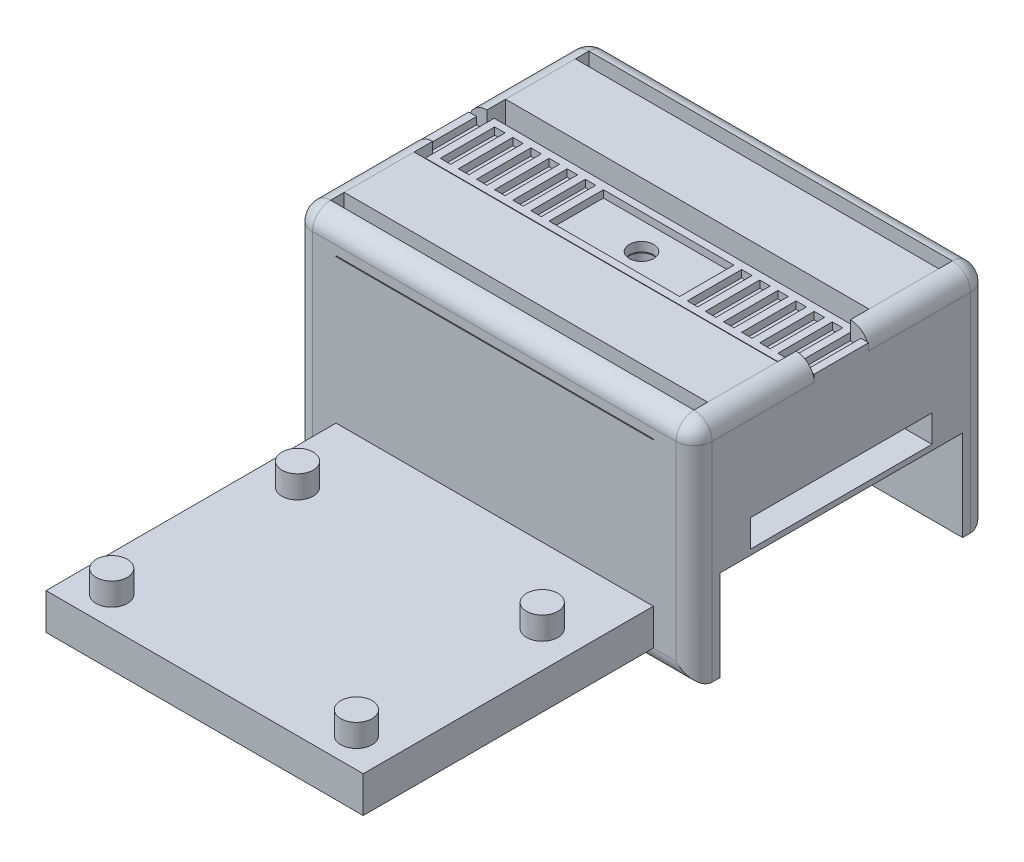
SolidWorks part; units mm, degrees
ref_plane "Front Plane" through (0, 0, 0) normal (0, 0, 1) x (1, 0, 0)
ref_plane "Top Plane" through (0, 0, 0) normal (0, 1, 0) x (1, 0, 0)
ref_plane "Right Plane" through (0, 0, 0) normal (1, 0, 0) x (0, 0, -1)
sketch "Sketch1" plane through (0, 0, 0) normal (0, 1, 0) x (1, 0, 0)
  line L1 (-22.05, 16.25) -> (22.05, 16.25)
  line L2 (-22.05, 16.25) -> (-22.05, -16.25)
  line L3 (-22.05, -16.25) -> (22.05, -16.25)
  line L4 (22.05, 16.25) -> (22.05, -16.25)
  line L5 (-22.05, 16.25) -> (22.05, -16.25) construction
  line L6 (-22.05, -16.25) -> (22.05, 16.25) construction
  point P0 (0, 0)
  dimension "D1" = 44.1
  dimension "D2" = 32.5
extrude "Boss-Extrude1" add sketch "Sketch1" along normal blind 25
sketch "Sketch2" plane through (0, 0, 0) normal (0, -1, 0) x (1, 0, 0)
  line L0 (22.05, 16.25) -> (22.05, -16.25) construction
  line L1 (-22.05, -13.375) -> (22.05, -13.375)
  line L2 (-22.05, -13.375) -> (-22.05, 13.375)
  line L3 (-22.05, 13.375) -> (22.05, 13.375)
  line L4 (22.05, -13.375) -> (22.05, 13.375)
  line L5 (-22.05, -13.375) -> (22.05, 13.375) construction
  line L6 (-22.05, 13.375) -> (22.05, -13.375) construction
  point P0 (0, 0)
  dimension "D1" = 26.75
extrude "Cut-Extrude1" cut sketch "Sketch2" against normal blind 10
fillet "Fillet1" radius 2 10 edges at (0, 25, -16.25) (22.05, 12.5, -16.25) (-22.05, 12.5, -16.25) (-22.05, 12.5, 16.25) (22.05, 12.5, 16.25) (0, 25, 16.25) (22.05, 25, 0) (-22.05, 25, 0) (0, 0, -16.25) (0, 0, 16.25)
sketch "Sketch6" plane through (0, 0, 0) normal (1, 0, 0) x (0, 0, -1)
  line L0 (14.25, 23) -> (-14.25, 23) construction
  line L1 (-10, 10.6) -> (10, 10.6)
  line L2 (-10, 10.6) -> (-10, 13.6)
  line L3 (-10, 13.6) -> (10, 13.6)
  line L4 (10, 10.6) -> (10, 13.6)
  line L5 (-10, 10.6) -> (10, 13.6) construction
  line L6 (-10, 13.6) -> (10, 10.6) construction
  line L12 (13.375, 10) -> (-13.375, 10) construction
  line L13 (-14.25, 25) -> (14.25, 25) construction
  line L14 (-3, 23) -> (3, 23)
  line L15 (-3, 23) -> (-3, 25)
  line L16 (-3, 25) -> (3, 25)
  line L17 (3, 23) -> (3, 25)
  line L18 (-3, 23) -> (3, 25) construction
  line L19 (-3, 25) -> (3, 23) construction
  point P0 (0, 12.1)
  point P8 (0, 10)
  point P11 (0, 24)
  point P20 (0, 23)
  dimension "D1" = 20
  dimension "D3" = 3
  dimension "D4" = 0.6
  dimension "D5" = 2
  dimension "D6" = 6
extrude "Cut-Extrude2" cut sketch "Sketch6" against normal through all both and the other way through all
sketch "Sketch7" plane through (0, 25, 0) normal (0, 1, 0) x (1, 0, 0)
  line L0 (-20.05, 14.25) -> (-20.05, 3) construction
  line L1 (-20.05, 5.05) -> (20.05, 5.05)
  line L2 (-20.05, 5.05) -> (-20.05, 3.8)
  line L3 (-20.05, 3.8) -> (20.05, 3.8)
  line L4 (20.05, 5.05) -> (20.05, 3.8)
  line L5 (20.05, 3) -> (20.05, 14.25) construction
  line L6 (-20.05, -3) -> (-20.05, -14.25) construction
  line L7 (-20.05, -3.8) -> (20.05, -3.8)
  line L8 (-20.05, -3.8) -> (-20.05, -5.05)
  line L9 (-20.05, -5.05) -> (20.05, -5.05)
  line L10 (20.05, -3.8) -> (20.05, -5.05)
  line L11 (20.05, -14.25) -> (20.05, -3) construction
  line L12 (-22.05, 3) -> (22.05, 3) construction
  line L13 (-22.05, -3) -> (22.05, -3) construction
  dimension "D1" = 1.25
  dimension "D2" = 0.8
  dimension "D3" = 0.8
  dimension "D4" = 1.25
extrude "Cut-Extrude3" cut sketch "Sketch7" against normal blind 5.5
sketch "Sketch8" plane through (0, 23, 0) normal (0, 1, 0) x (1, 0, 0)
  line L0 (0, 11.2553) -> (0, -14.25) construction
  line L1 (-20.05, -14.25) -> (20.05, -14.25) construction
  line L2 (-22.05, -3) -> (22.05, -3) construction
  line L3 (-22.05, 3) -> (-21.2, 3)
  line L4 (-22.05, 3) -> (-22.05, -3)
  line L5 (-22.05, -3) -> (-21.2, -3)
  line L6 (-21.2, 3) -> (-21.2, -3)
  line L7 (22.05, 3) -> (22.05, -3)
  line L8 (22.05, 3) -> (21.2, 3)
  line L9 (21.2, 3) -> (21.2, -3)
  line L10 (22.05, -3) -> (21.2, -3)
  line L11 (-22.05, 3) -> (22.05, 3) construction
  line L12 (-20.05, 3) -> (-19.2, 3)
  line L13 (-20.05, 3) -> (-20.05, -3)
  line L14 (-20.05, -3) -> (-19.2, -3)
  line L15 (-19.2, 3) -> (-19.2, -3)
  line L16 (20.05, 3) -> (20.05, -3)
  line L17 (20.05, 3) -> (19.2, 3)
  line L18 (19.2, 3) -> (19.2, -3)
  line L19 (20.05, -3) -> (19.2, -3)
  line L20 (-20.05, 3) -> (20.05, 3) construction
  line L21 (-18.05, 3) -> (-17.2, 3)
  line L22 (-18.05, 3) -> (-18.05, -3)
  line L23 (-18.05, -3) -> (-17.2, -3)
  line L24 (-17.2, 3) -> (-17.2, -3)
  line L25 (-20.05, -3) -> (20.05, -3) construction
  line L26 (18.05, 3) -> (18.05, -3)
  line L27 (18.05, 3) -> (17.2, 3)
  line L28 (17.2, 3) -> (17.2, -3)
  line L29 (18.05, -3) -> (17.2, -3)
  line L30 (16.05, 3) -> (16.05, -3)
  line L31 (-16.05, 3) -> (-15.2, 3)
  line L32 (-16.05, 3) -> (-16.05, -3)
  line L33 (-16.05, -3) -> (-15.2, -3)
  line L34 (-15.2, 3) -> (-15.2, -3)
  line L35 (16.05, 3) -> (15.2, 3)
  line L36 (15.2, 3) -> (15.2, -3)
  line L37 (16.05, -3) -> (15.2, -3)
  line L38 (14.05, 3) -> (14.05, -3)
  line L39 (-14.05, 3) -> (-13.2, 3)
  line L40 (-14.05, 3) -> (-14.05, -3)
  line L41 (-14.05, -3) -> (-13.2, -3)
  line L42 (-13.2, 3) -> (-13.2, -3)
  line L43 (14.05, 3) -> (13.2, 3)
  line L44 (13.2, 3) -> (13.2, -3)
  line L45 (14.05, -3) -> (13.2, -3)
  line L46 (12.05, 3) -> (12.05, -3)
  line L47 (-12.05, 3) -> (-11.2, 3)
  line L48 (-12.05, 3) -> (-12.05, -3)
  line L49 (-12.05, -3) -> (-11.2, -3)
  line L50 (-11.2, 3) -> (-11.2, -3)
  line L51 (12.05, 3) -> (11.2, 3)
  line L52 (11.2, 3) -> (11.2, -3)
  line L53 (12.05, -3) -> (11.2, -3)
  line L54 (10.05, 3) -> (10.05, -3)
  line L55 (-10.05, 3) -> (-9.2, 3)
  line L56 (-10.05, 3) -> (-10.05, -3)
  line L57 (-10.05, -3) -> (-9.2, -3)
  line L58 (-9.2, 3) -> (-9.2, -3)
  line L59 (10.05, 3) -> (9.2, 3)
  line L60 (9.2, 3) -> (9.2, -3)
  line L61 (10.05, -3) -> (9.2, -3)
  line L62 (8.05, 3) -> (8.05, -3)
  line L63 (-8.05, 3) -> (-7.2, 3)
  line L64 (-8.05, 3) -> (-8.05, -3)
  line L65 (-8.05, -3) -> (-7.2, -3)
  line L66 (-7.2, 3) -> (-7.2, -3)
  line L67 (8.05, 3) -> (7.2, 3)
  line L68 (7.2, 3) -> (7.2, -3)
  line L69 (8.05, -3) -> (7.2, -3)
  point P77 (-13.625, 3)
  point P78 (-11.625, 3)
  point P79 (-21.625, 3)
  point P80 (-19.625, 3)
  point P81 (-17.625, 3)
  point P82 (-15.625, 3)
  point P83 (-9.625, 3)
  point P84 (-7.625, 3)
  dimension "D1" = 0.85
  dimension "D2" = 2
  dimension "D3" = 2
  dimension "D4" = 2
  dimension "D5" = 2
  dimension "D6" = 2
  dimension "D7" = 2
  dimension "D8" = 2
extrude "Boss-Extrude3" add sketch "Sketch8" along normal blind 0.8
sketch "Sketch9" plane through (0, 23, 0) normal (0, 1, 0) x (1, 0, 0)
  circle A0 centre (0, 0) radius 1.35
  dimension "D1" = 2.7
extrude "Cut-Extrude4" cut sketch "Sketch9" against normal blind 4
sketch "Sketch11" plane through (0, 0, 3) normal (0, 0, -1) x (-1, 0, 0)
  line L1 (-20.05, 25) -> (20.05, 25)
  line L2 (-20.05, 25) -> (-20.05, 23.8)
  line L3 (-20.05, 23.8) -> (20.05, 23.8)
  line L4 (20.05, 25) -> (20.05, 23.8)
extrude "Cut-Extrude5" cut sketch "Sketch11" against normal up to surface (0.8 mm away) up to face at (0, 22.25, 3.8)
sketch "Sketch12" plane through (0, 0, -3) normal (0, 0, 1) x (1, 0, 0)
  line L1 (-20.05, 25) -> (20.05, 25)
  line L2 (-20.05, 25) -> (-20.05, 23.8)
  line L3 (-20.05, 23.8) -> (20.05, 23.8)
  line L4 (20.05, 25) -> (20.05, 23.8)
extrude "Cut-Extrude6" cut sketch "Sketch12" against normal up to surface (0.8 mm away) up to face at (0, 22.25, -3.8)
sketch "Sketch13" plane through (0, 0, -16.25) normal (0, 0, -1) x (-1, 0, 0)
  line L1 (-17.55, 22) -> (17.45, 22)
  line L2 (-17.55, 22) -> (-17.55, 21.9)
  line L3 (-17.55, 21.9) -> (17.45, 21.9)
  line L4 (17.45, 22) -> (17.45, 21.9)
  line L5 (20.05, 23) -> (-20.05, 23) construction
  line L6 (-20.05, 23) -> (-20.05, 2) construction
  dimension "D1" = 0.1
  dimension "D2" = 1
  dimension "D3" = 35
  dimension "D4" = 2.5
extrude "Cut-Extrude8" cut sketch "Sketch13" against normal through all
sketch "Sketch14" plane through (0, 0, 16.25) normal (0, 0, 1) x (1, 0, 0)
  line L0 (-17.45, 6) -> (17.55, 6)
  line L1 (17.55, 6) -> (17.55, 2)
  line L2 (17.55, 2) -> (-17.45, 2)
  line L3 (-17.45, 2) -> (-17.45, 6)
  line L4 (17.55, 22) -> (17.55, 21.9) construction
  line L5 (22.05, 0) -> (-22.05, 0) construction
  dimension "D1" = 4
  dimension "D2" = 2
  dimension "D3" = 35
  dimension "D4" = 0
extrude "Boss-Extrude4" add sketch "Sketch14" along normal blind 32
sketch "Sketch15" plane through (0, 6, 0) normal (0, 1, 0) x (1, 0, 0)
  line L0 (-17.45, -48.25) -> (-17.45, -16.25) construction
  line L3 (17.55, -48.25) -> (-17.45, -48.25) construction
  circle A0 centre (-13.45, -24.5) radius 1.725
  circle A1 centre (13.55, -24.5) radius 1.725
  circle A2 centre (13.55, -45) radius 1.725
  circle A3 centre (-13.45, -45) radius 1.725
  dimension "D3" = 3.45
  dimension "D1" = 27
  dimension "D2" = 20.5
  dimension "D4" = 4
  dimension "D5" = 3.25
extrude "Boss-Extrude5" add sketch "Sketch15" along normal blind 2.5
sketch "Sketch16" plane through (0, 25, 0) normal (0, 1, 0) x (1, 0, 0)
  line L0 (20.05, 5.05) -> (20.05, 14.25) construction
  line L1 (-20.05, 14.25) -> (20.05, 14.25)
  line L2 (-20.05, 14.25) -> (-20.05, 12.75)
  line L3 (-20.05, 12.75) -> (20.05, 12.75)
  line L4 (20.05, 14.25) -> (20.05, 12.75)
  line L5 (20.05, -14.25) -> (20.05, -5.05) construction
  line L6 (-20.05, -14.25) -> (20.05, -14.25)
  line L7 (-20.05, -14.25) -> (-20.05, -12.75)
  line L8 (-20.05, -12.75) -> (20.05, -12.75)
  line L9 (20.05, -14.25) -> (20.05, -12.75)
  dimension "D1" = 1.5
  dimension "D2" = 1.5
extrude "Cut-Extrude9" cut sketch "Sketch16" against normal blind 5
